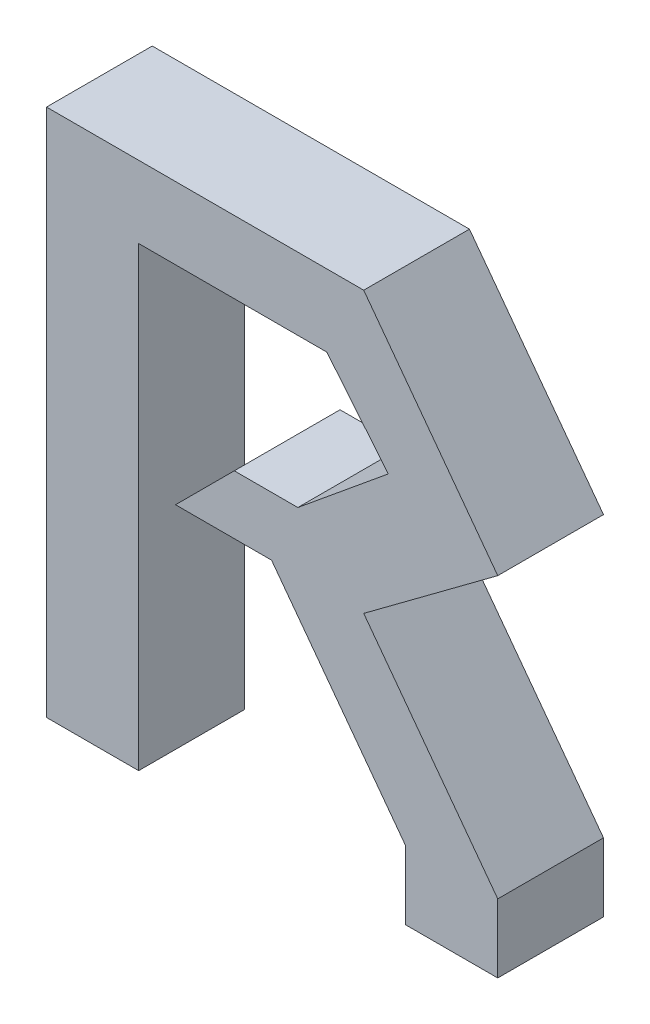
SolidWorks part; units mm, degrees
ref_plane "Front Plane" through (0, 0, 0) normal (0, 0, 1) x (1, 0, 0)
ref_plane "Top Plane" through (0, 0, 0) normal (0, 1, 0) x (1, 0, 0)
ref_plane "Right Plane" through (0, 0, 0) normal (1, 0, 0) x (0, 0, -1)
sketch "Sketch1" plane through (0, 0, 0) normal (0, 0, 1) x (1, 0, 0)
  line L0 (-308.0482, 51.5335) -> (-308.0482, -48.4665)
  line L1 (-308.0482, 51.5335) -> (-248.0482, 51.5335)
  line L2 (-248.0482, 51.5335) -> (-222.6946, 17.4426)
  line L3 (-222.6946, 17.4426) -> (-248.0482, -1.4129)
  line L4 (-248.0482, -1.4129) -> (-222.6946, -35.5039)
  line L5 (-222.6946, -35.5039) -> (-222.6946, -48.4665)
  line L6 (-222.6946, -48.4665) -> (-240.1245, -48.4665)
  line L7 (-240.1245, -48.4665) -> (-240.1245, -35.5039)
  line L8 (-240.1245, -35.5039) -> (-265.478, -1.4129)
  line L9 (-265.478, -1.4129) -> (-283.6446, -1.4129)
  line L10 (-283.6446, -1.4129) -> (-272.5297, 9.7019)
  line L11 (-308.0482, -48.4665) -> (-290.6183, -48.4665)
  line L12 (-290.6183, -48.4665) -> (-290.6183, 37.8971)
  line L13 (-290.6183, 37.8971) -> (-255.0178, 37.8971)
  line L14 (-255.0178, 37.8971) -> (-243.4017, 23.7557)
  line L15 (-243.4017, 23.7557) -> (-260.5106, 9.7019)
  line L16 (-260.5106, 9.7019) -> (-272.5297, 9.7019)
extrude "Boss-Extrude1" add sketch "Sketch1" along normal blind 20 contours L1 L2 L3 L4 L5 L6 L7 L8 L9 L10 L16 L15 L14 L13 L12 L11 L0
